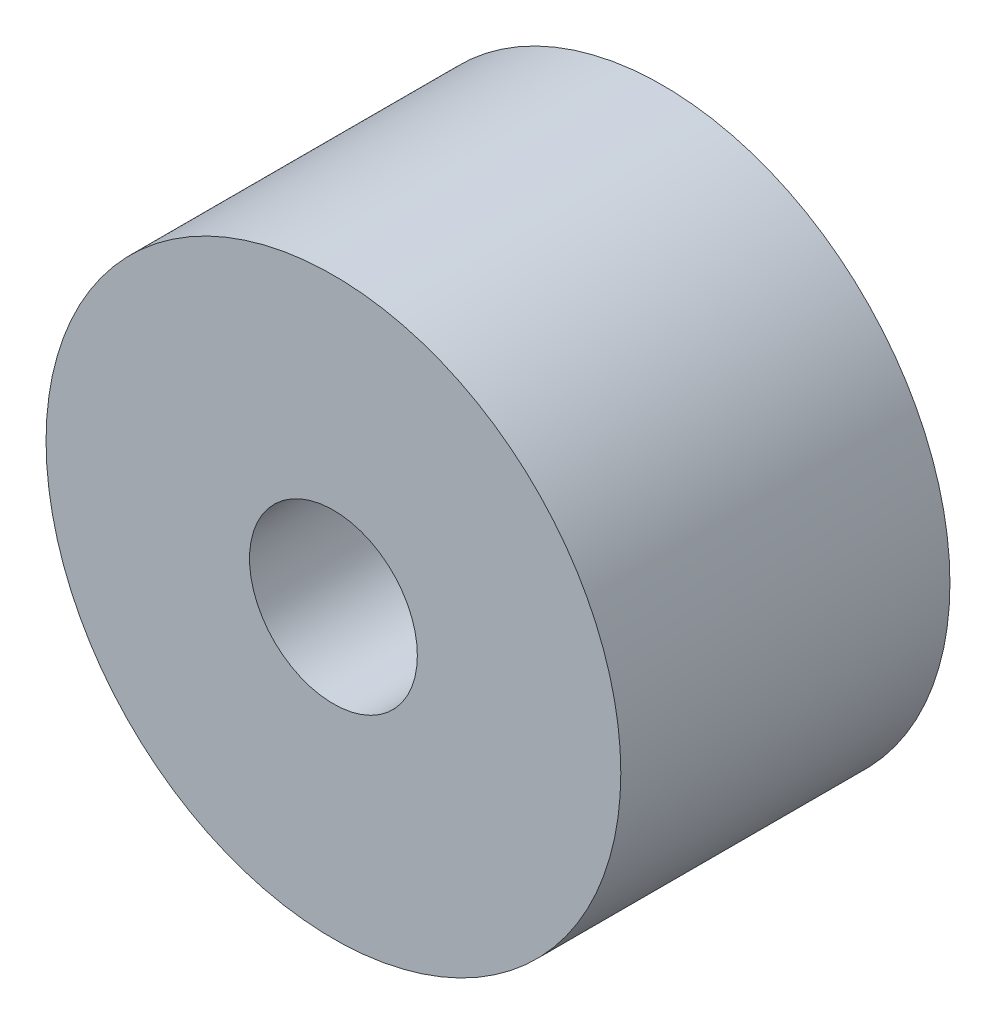
SolidWorks part; units mm, degrees
material "ABS"
ref_plane "Front Plane" through (0, 0, 0) normal (0, 0, 1) x (1, 0, 0)
ref_plane "Top Plane" through (0, 0, 0) normal (0, 1, 0) x (1, 0, 0)
ref_plane "Right Plane" through (0, 0, 0) normal (1, 0, 0) x (0, 0, -1)
sketch "Sketch1" plane through (0, 0, 0) normal (0, 0, 1) x (1, 0, 0)
  circle A0 centre (0, 0) radius 8.7312
  circle A1 centre (0, 0) radius 2.55
  dimension "D1" = 5.1
  dimension "D2" = 17.4625
extrude "Boss-Extrude1" add sketch "Sketch1" along normal blind 10
